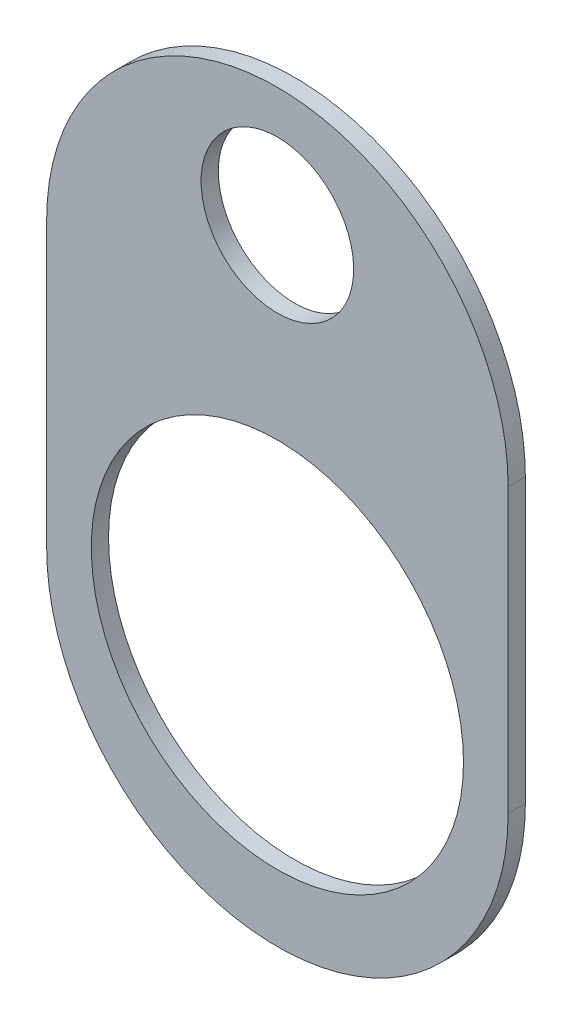
SolidWorks part; units mm, degrees
ref_plane "Front Plane" through (0, 0, 0) normal (0, 0, 1) x (1, 0, 0)
ref_plane "Top Plane" through (0, 0, 0) normal (0, 1, 0) x (1, 0, 0)
ref_plane "Right Plane" through (0, 0, 0) normal (1, 0, 0) x (0, 0, -1)
sketch "Sketch2" plane through (0, 0, 0) normal (0, 0, 1) x (1, 0, 0)
  line L0 (0, 0) -> (0, 19.304)
  line L1 (31.496, 0) -> (31.496, 19.304)
  arc A0 (0, 19.304) -> (31.496, 19.304) centre (15.748, 19.304) cw
  arc A1 (31.496, 0) -> (0, 0) centre (15.748, 0) cw
  point P7 (15.748, 35.052)
  point P8 (15.748, -15.748)
  dimension "D2" = 50.8
  dimension "D1" = 31.496
extrude "Fastener Body" add sketch "Sketch2" against normal blind 1.176
sketch "Sketch3" plane through (0, 0, 0) normal (0, 0, 1) x (1, 0, 0)
  circle A0 centre (15.748, 26.9022) radius 5.207
  circle A1 centre (15.748, 1.5022) radius 12.7
  point P4 (15.748, 25.8597)
  dimension "D1" = 10.414
  dimension "D2" = 25.4
  dimension "D3" = 25.4
extrude "Cut-Extrude2" cut sketch "Sketch3" against normal up to next
